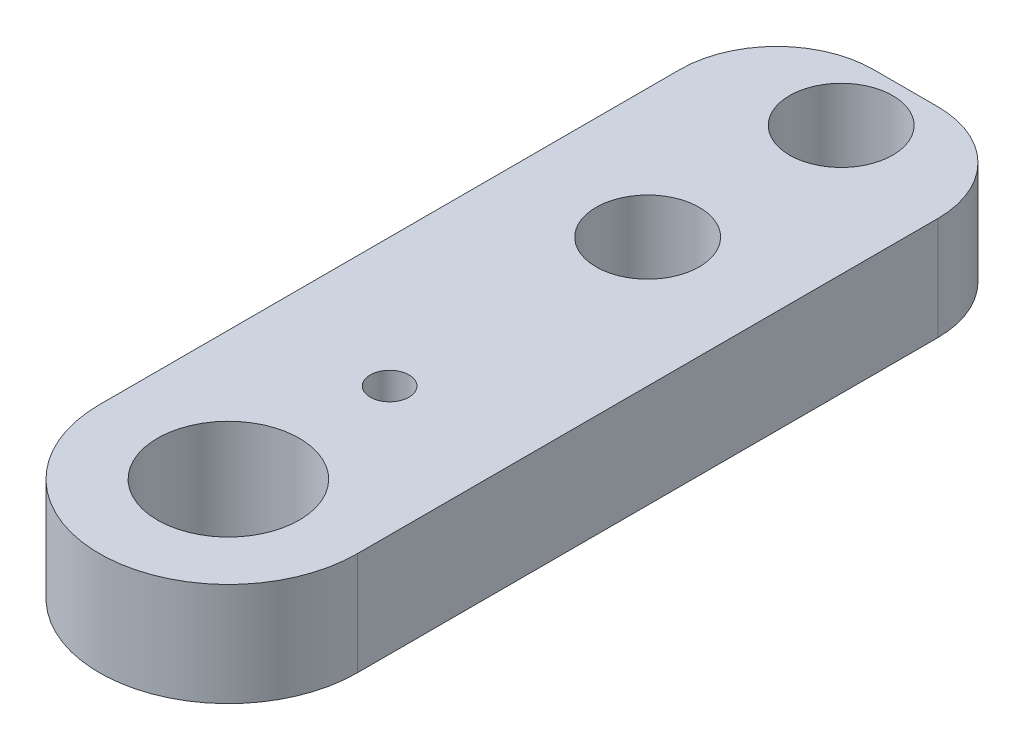
SolidWorks part; units mm, degrees
ref_plane "前视基准面" through (0, 0, 0) normal (0, 0, 1) x (1, 0, 0)
ref_plane "上视基准面" through (0, 0, 0) normal (0, 1, 0) x (1, 0, 0)
ref_plane "右视基准面" through (0, 0, 0) normal (1, 0, 0) x (0, 0, -1)
other "Configuration Table"
sketch "草图1" plane through (0, 0, 0) normal (0, 1, 0) x (1, 0, 0)
  line L0 (0, -14.0115) -> (0, 21.093) construction
  line L1 (-4, -9.0861) -> (-4, 8.9139)
  line L2 (-1, 11.9139) -> (1, 11.9139)
  line L3 (4, 8.9139) -> (4, -9.0861)
  arc A0 (-4, -9.0861) -> (4, -9.0861) centre (0, -9.0861) ccw
  circle A1 centre (0, 9.9139) radius 1.6
  circle A2 centre (0, -9.0861) radius 2.2
  circle A3 centre (0, 3.9139) radius 1.6
  arc A4 (1, 11.9139) -> (4, 8.9139) centre (1, 8.9139) cw
  arc A5 (-4, 8.9139) -> (-1, 11.9139) centre (-1, 8.9139) cw
  circle A6 centre (0, -4.0861) radius 0.6
  point P17 (-4, 11.9139)
  dimension "D1" = 8
  dimension "D3" = 4.4
  dimension "D4" = 3.2
  dimension "D5" = 3.2
  dimension "D6" = 6
  dimension "D7" = 2
  dimension "D8" = 3
  dimension "D9" = 1.2
  dimension "D10" = 5
  dimension "D2" = 21
extrude "凸台-拉伸1" add sketch "草图1" along normal blind 3.2
